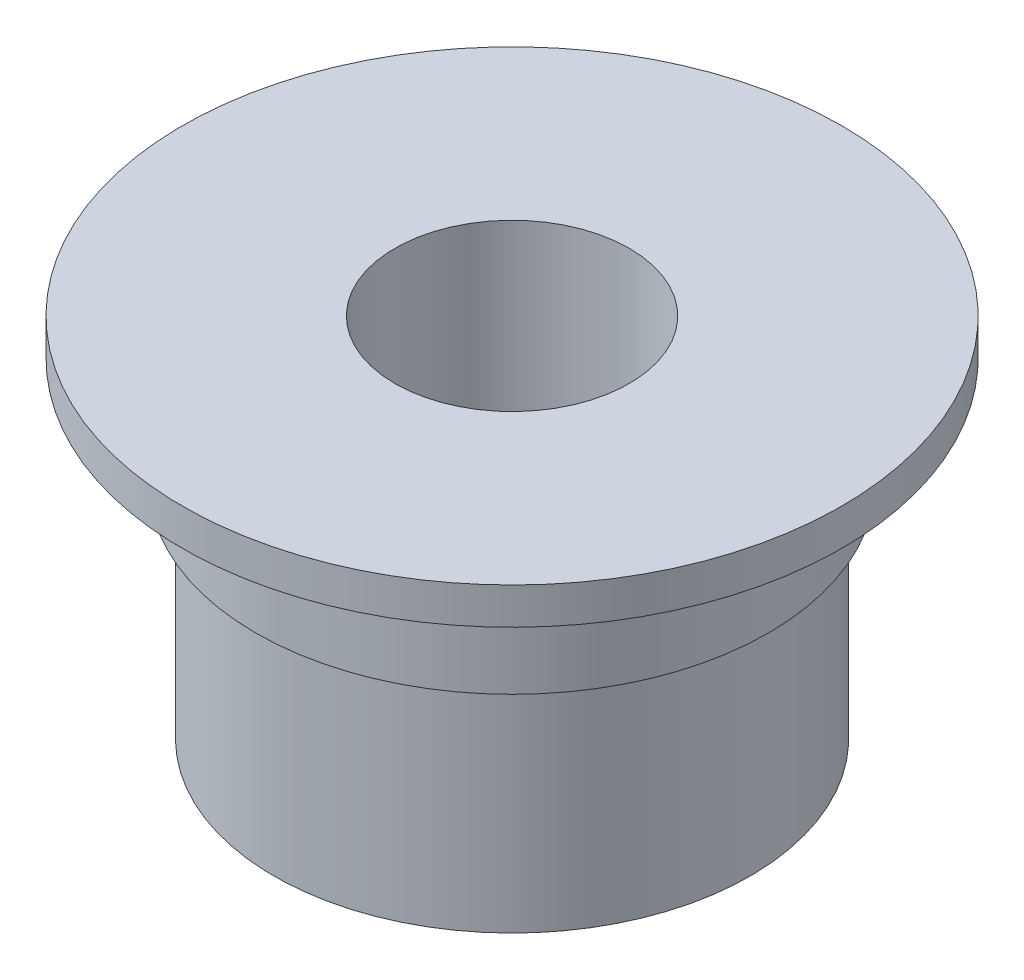
SolidWorks part; units mm, degrees
ref_plane "前视基准面" through (0, 0, 0) normal (0, 0, 1) x (1, 0, 0)
ref_plane "上视基准面" through (0, 0, 0) normal (0, 1, 0) x (1, 0, 0)
ref_plane "右视基准面" through (0, 0, 0) normal (1, 0, 0) x (0, 0, -1)
other "Configuration Table"
sketch "草图1" plane through (0, 0, 0) normal (0, 0, 1) x (1, 0, 0)
  line L0 (3.2, 0) -> (6.5, 0)
  line L1 (6.5, 0) -> (6.5, 6)
  line L2 (6.5, 6) -> (7, 6)
  line L3 (7, 6) -> (7, 9)
  line L4 (7, 9) -> (9, 9)
  line L5 (9, 9) -> (9, 10)
  line L6 (9, 10) -> (3.2, 10)
  line L7 (3.2, 10) -> (3.2, 0)
  line L8 (0, 0) -> (0, 10) construction
  dimension "x0" = 3.2
  dimension "x1" = 6.5
  dimension "x3" = 7
  dimension "x5" = 9
  dimension "y2" = 6
  dimension "y4" = 9
  dimension "y6" = 10
  dimension "y9" = 10
revolve "Cable_gland_section" add sketch "草图1" angle 360 about L8
